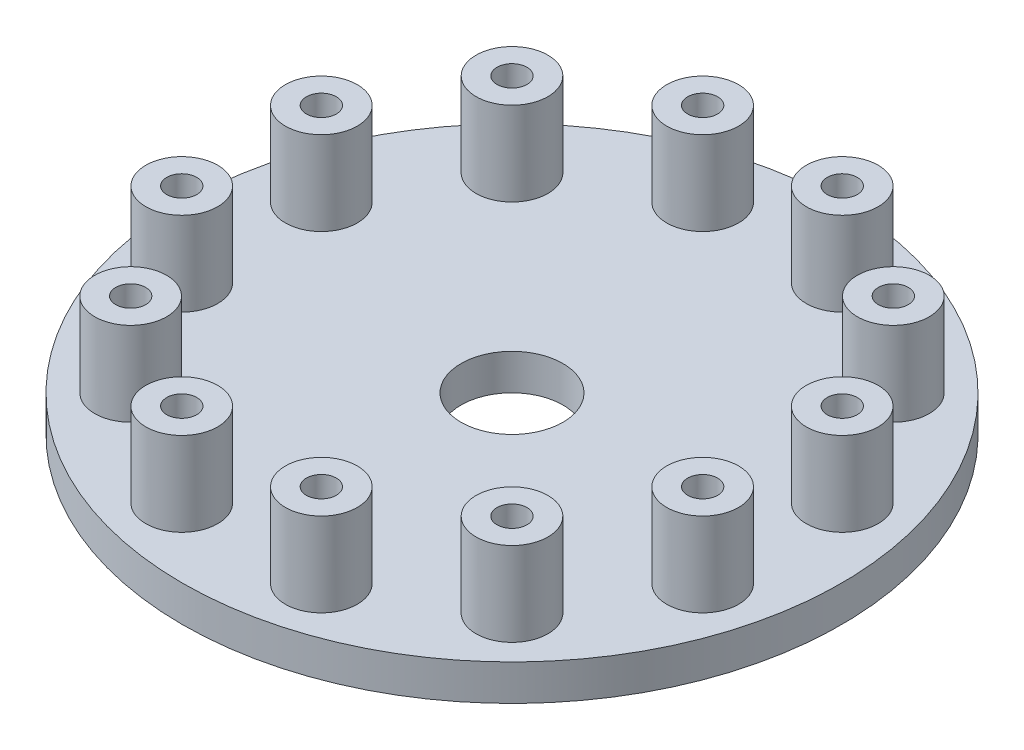
SolidWorks part; units mm, degrees
ref_plane "Front Plane" through (0, 0, 0) normal (0, 0, 1) x (1, 0, 0)
ref_plane "Top Plane" through (0, 0, 0) normal (0, 1, 0) x (1, 0, 0)
ref_plane "Right Plane" through (0, 0, 0) normal (1, 0, 0) x (0, 0, -1)
sketch "Sketch1" plane through (0, 0, 0) normal (0, 1, 0) x (1, 0, 0)
  line L0 (0, 0) -> (0, 29.921) construction
  line L1 (0, 0) -> (5.8234, 21.7333) construction
  line L2 (-5.8234, 21.7333) -> (0, 0) construction
  circle A0 centre (0, 0) radius 22.5 construction
  circle A1 centre (21.7333, -5.8234) radius 3
  circle A2 centre (15.9099, -15.9099) radius 3
  circle A3 centre (5.8234, -21.7333) radius 3
  circle A4 centre (-5.8234, -21.7333) radius 3
  circle A5 centre (-15.9099, -15.9099) radius 3
  circle A6 centre (-21.7333, -5.8234) radius 3
  circle A7 centre (-21.7333, 5.8234) radius 3
  circle A8 centre (-15.9099, 15.9099) radius 3
  circle A9 centre (-5.8234, 21.7333) radius 3
  circle A10 centre (5.8234, 21.7333) radius 3
  circle A11 centre (15.9099, 15.9099) radius 3
  circle A12 centre (21.7333, 5.8234) radius 3
  circle A49 centre (-1.2, 0) radius 10 construction
  circle A50 centre (1.2, 0) radius 10 construction
  circle A51 centre (0, 0) radius 27.5
  circle A52 centre (0, 0) radius 4.25
  dimension "D1" = 6
  dimension "D3" = 45
  dimension "D6" = 20
  dimension "D8" = 55
  dimension "D9" = 8.5
  dimension "D4" = 1.2
  dimension "D5" = 2.4
  dimension "D7" = 15
  dimension "D2" = 12
extrude "Boss-Extrude1" add sketch "Sketch1" along normal blind 3
sketch "Sketch2" plane through (0, 0, 0) normal (0, -1, 0) x (1, 0, 0)
  circle A0 centre (15.9099, 15.9099) radius 3 construction
  circle A1 centre (21.7333, 5.8234) radius 3 construction
  circle A2 centre (21.7333, -5.8234) radius 3 construction
  circle A3 centre (15.9099, -15.9099) radius 3 construction
  circle A4 centre (5.8234, -21.7333) radius 3 construction
  circle A5 centre (-5.8234, -21.7333) radius 3 construction
  circle A6 centre (-15.9099, -15.9099) radius 3 construction
  circle A7 centre (-21.7333, -5.8234) radius 3 construction
  circle A8 centre (-21.7333, 5.8234) radius 3 construction
  circle A9 centre (-15.9099, 15.9099) radius 3 construction
  circle A10 centre (-5.8234, 21.7333) radius 3 construction
  circle A11 centre (5.8234, 21.7333) radius 3 construction
  circle A12 centre (15.9099, 15.9099) radius 3
  circle A13 centre (21.7333, 5.8234) radius 3
  circle A14 centre (21.7333, -5.8234) radius 3
  circle A15 centre (15.9099, -15.9099) radius 3
  circle A16 centre (5.8234, -21.7333) radius 3
  circle A17 centre (-5.8234, -21.7333) radius 3
  circle A18 centre (-15.9099, -15.9099) radius 3
  circle A19 centre (-21.7333, -5.8234) radius 3
  circle A20 centre (-21.7333, 5.8234) radius 3
  circle A21 centre (-15.9099, 15.9099) radius 3
  circle A22 centre (-5.8234, 21.7333) radius 3
  circle A23 centre (5.8234, 21.7333) radius 3
extrude "Boss-Extrude2" add sketch "Sketch2" against normal blind 10
hole_wizard "M3 Tapped Hole1" positions "Sketch3" profile "Sketch4" tap size "M3" standard "ISO" end condition through all
sketch "Sketch3" plane through (0, 10, 0) normal (0, 1, 0) x (1, 0, 0)
  point P0 (-5.8234, 21.7333)
sketch "Sketch4" plane through (-5.8234, 10, -21.7333) normal (1, 0, 0) x (0, 0, 1)
  line L0 (0, 0) -> (0, 10)
  line L1 (0, 10) -> (1.25, 10)
  line L2 (1.25, 10) -> (1.25, 0)
  line L5 (1.25, 0) -> (0, 0)
  line L11 (0, -6.35) -> (0, 107.95) construction
  dimension "Thru Tap Drill Dia." = 2.5
  dimension "Thru Tap Drill Depth" = 10
cosmetic thread "Hole Thread1" parameters "D2"=3
pattern_circular "CirPattern1" count 12 over 360 about axis through (0, 0, 0) along (0, 1, 0) of "M3 Tapped Hole1"
cosmetic thread "Hole Thread2" parameters "D2"=3
cosmetic thread "Hole Thread3" parameters "D2"=3
cosmetic thread "Hole Thread4" parameters "D2"=3
cosmetic thread "Hole Thread5" parameters "D2"=3
cosmetic thread "Hole Thread6" parameters "D2"=3
cosmetic thread "Hole Thread7" parameters "D2"=3
cosmetic thread "Hole Thread8" parameters "D2"=3
cosmetic thread "Hole Thread9" parameters "D2"=3
cosmetic thread "Hole Thread10" parameters "D2"=3
cosmetic thread "Hole Thread11" parameters "D2"=3
cosmetic thread "Hole Thread12" parameters "D2"=3
equation "\"N\"= 12'N - Number of rollers"
equation "\"Rr\"= 3'Rr - Radius of the roller"
equation "\"R\"= 45 / 2'R - Radius of the rollers PCD (Pitch Circle Diamater)"
equation "\"E\"= 1.2'E <Rr ; E - Eccentricity - offset from input shaft to a cycloidal disk"
equation "\"D2@Sketch1\"= \"N\""
equation "\"D1@Sketch1\" = \"Rr * 2\""
equation "\"D3@Sketch1\"= \"R\" * 2"
equation "\"D4@Sketch1\"= \"E\""
